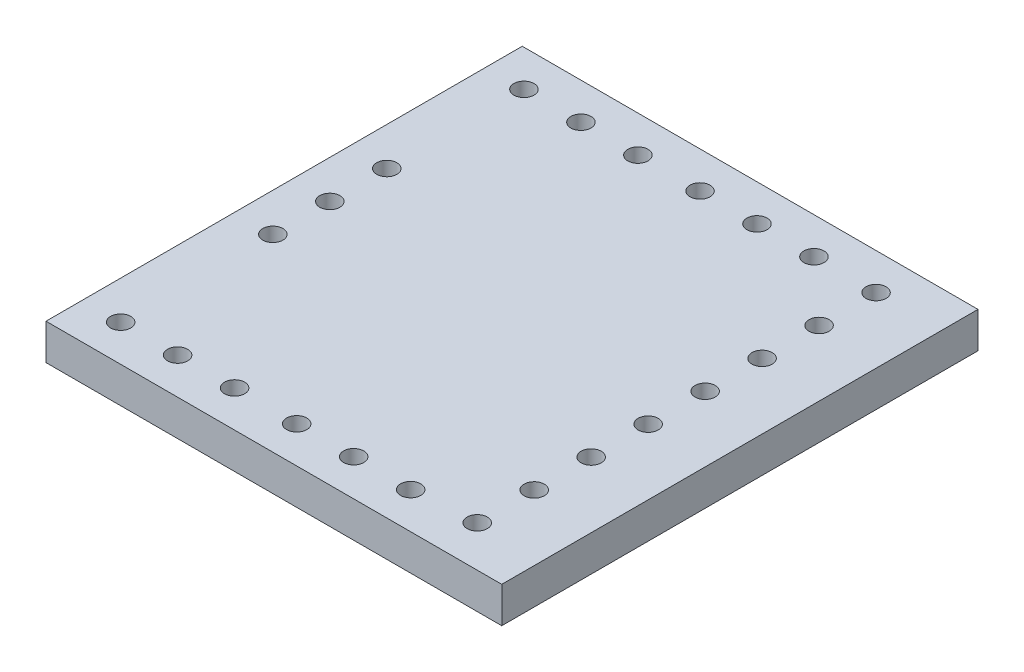
SolidWorks part; units mm, degrees
ref_plane "Front" through (0, 0, 0) normal (0, 0, 1) x (1, 0, 0)
ref_plane "Top" through (0, 0, 0) normal (0, 1, 0) x (1, 0, 0)
ref_plane "Right" through (0, 0, 0) normal (1, 0, 0) x (0, 0, -1)
sketch "Эскиз1" plane through (0, 0, 0) normal (0, 1, 0) x (1, 0, 0)
  line L1 (-10.16, 10.617) -> (10.16, 10.617)
  line L2 (-10.16, 10.617) -> (-10.16, -10.617)
  line L3 (-10.16, -10.617) -> (10.16, -10.617)
  line L4 (10.16, 10.617) -> (10.16, -10.617)
  line L5 (-10.16, 10.617) -> (10.16, -10.617) construction
  line L6 (-10.16, -10.617) -> (10.16, 10.617) construction
  point P0 (0, 0)
  dimension "D1" = 20.32
  dimension "D2" = 21.234
extrude "Бобышка-Вытянуть1" add sketch "Эскиз1" along normal blind 1.6
sketch "Эскиз3" plane through (0, 1.6, 0) normal (0, 1, 0) x (1, 0, 0)
  line L0 (-10.16, 10.617) -> (-10.16, -10.617) construction
  line L1 (10.16, 10.617) -> (-10.16, 10.617) construction
  line L2 (0, 0) -> (6.2207, 0) construction
  line L3 (10.16, -10.617) -> (10.16, 10.617) construction
  circle A0 centre (-8.458, 8.991) radius 0.45
  circle A1 centre (-5.918, 8.991) radius 0.45
  circle A2 centre (-3.378, 8.991) radius 0.45
  circle A3 centre (-0.608, 8.991) radius 0.45
  circle A4 centre (1.932, 8.991) radius 0.45
  circle A5 centre (4.472, 8.991) radius 0.45
  circle A6 centre (4.472, -8.991) radius 0.45
  circle A7 centre (1.932, -8.991) radius 0.45
  circle A8 centre (-0.608, -8.991) radius 0.45
  circle A9 centre (-3.378, -8.991) radius 0.45
  circle A10 centre (-5.918, -8.991) radius 0.45
  circle A11 centre (-8.458, -8.991) radius 0.45
  circle A12 centre (7.239, 8.991) radius 0.45
  circle A13 centre (7.239, 6.451) radius 0.45
  circle A14 centre (7.239, 3.911) radius 0.45
  circle A15 centre (7.239, 1.371) radius 0.45
  circle A16 centre (7.239, -1.169) radius 0.45
  circle A17 centre (7.239, -3.709) radius 0.45
  circle A18 centre (7.239, -6.249) radius 0.45
  circle A19 centre (7.239, -8.789) radius 0.45
  circle A20 centre (-8.457, 2.875) radius 0.45
  circle A21 centre (-8.457, 0.335) radius 0.45
  circle A22 centre (-8.457, -2.205) radius 0.45
  dimension "D3" = 0.9
  dimension "D6" = 0.9
  dimension "D9" = 0.9
  dimension "D1" = 1.702
  dimension "D2" = 1.626
  dimension "D7" = 1.626
  dimension "D8" = 2.921
  dimension "D10" = 7.742
  dimension "D11" = 1.703
  dimension "D4" = 3
  dimension "D5" = 2
extrude "Вырез-Вытянуть1" cut sketch "Эскиз3" against normal through all
